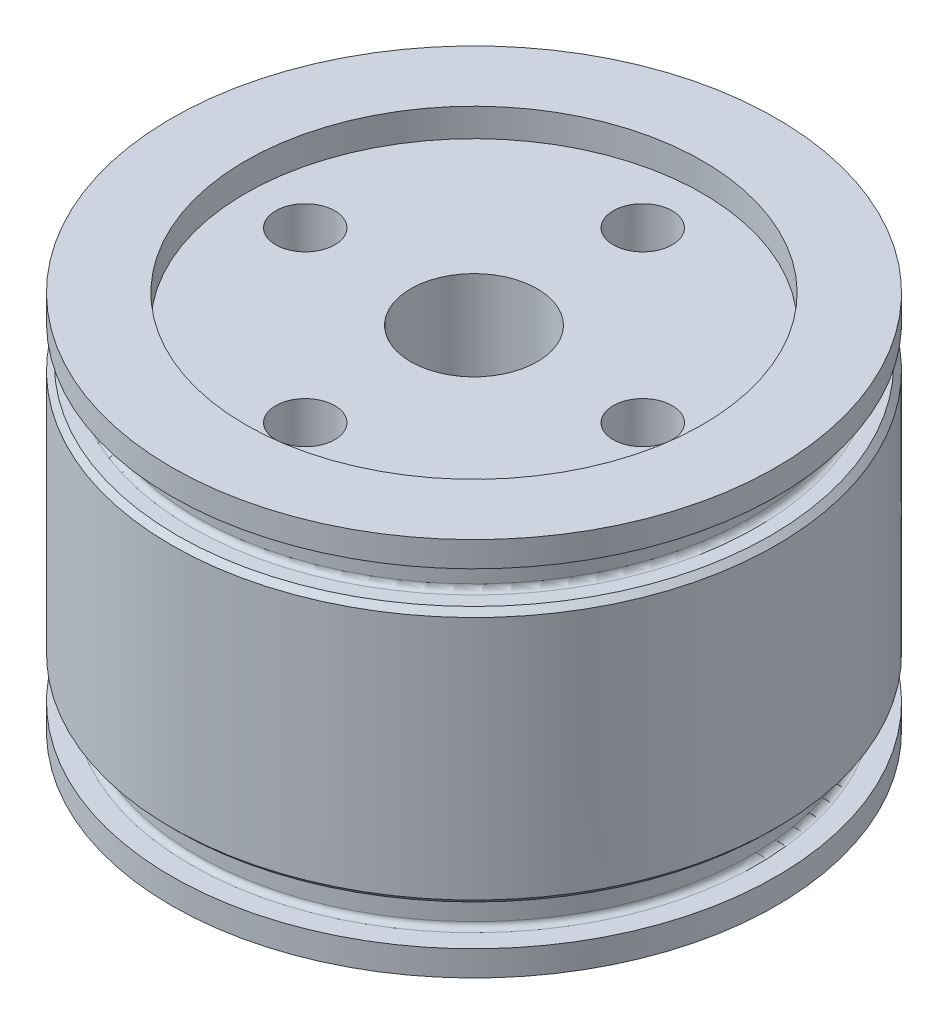
SolidWorks part; units mm, degrees
ref_plane "Front Plane" through (0, 0, 0) normal (0, 0, 1) x (1, 0, 0)
ref_plane "Top Plane" through (0, 0, 0) normal (0, 1, 0) x (1, 0, 0)
ref_plane "Right Plane" through (0, 0, 0) normal (1, 0, 0) x (0, 0, -1)
sketch "Sketch1" plane through (0, 0, 0) normal (0, 1, 0) x (1, 0, 0)
  line L0 (0, 0) -> (0, 12) construction
  circle A0 centre (0, 0) radius 21.5
  circle A1 centre (0, 0) radius 4.5
  circle A2 centre (0, 12) radius 2.1
  circle A3 centre (12, 0) radius 2.1
  circle A4 centre (0, -12) radius 2.1
  circle A5 centre (-12, 0) radius 2.1
  point P15 (0, 0)
  dimension "D1" = 43
  dimension "D2" = 9
  dimension "D5" = 4.2
  dimension "D3" = 12
  dimension "D4" = 12
  dimension "D6" = 4
extrude "Boss-Extrude1" add sketch "Sketch1" along normal blind 27
sketch "Sketch2" plane through (0, 0, 0) normal (0, -1, 0) x (1, 0, 0)
  line L0 (12, -4.1569) -> (15.6, -2.0785)
  line L1 (4.1569, 12) -> (2.0785, 15.6)
  line L2 (2.0785, 15.6) -> (-2.0785, 15.6)
  line L3 (-2.0785, 15.6) -> (-4.1569, 12)
  line L4 (-4.1569, 12) -> (-2.0785, 8.4)
  line L5 (-2.0785, 8.4) -> (2.0785, 8.4)
  line L6 (2.0785, 8.4) -> (4.1569, 12)
  line L7 (15.6, -2.0785) -> (15.6, 2.0785)
  line L8 (15.6, 2.0785) -> (12, 4.1569)
  line L9 (12, 4.1569) -> (8.4, 2.0785)
  line L10 (8.4, 2.0785) -> (8.4, -2.0785)
  line L11 (8.4, -2.0785) -> (12, -4.1569)
  line L12 (-4.1569, -12) -> (-2.0785, -15.6)
  line L13 (-2.0785, -15.6) -> (2.0785, -15.6)
  line L14 (2.0785, -15.6) -> (4.1569, -12)
  line L15 (4.1569, -12) -> (2.0785, -8.4)
  line L16 (2.0785, -8.4) -> (-2.0785, -8.4)
  line L17 (-2.0785, -8.4) -> (-4.1569, -12)
  line L18 (-12, 4.1569) -> (-15.6, 2.0785)
  line L19 (-15.6, 2.0785) -> (-15.6, -2.0785)
  line L20 (-15.6, -2.0785) -> (-12, -4.1569)
  line L21 (-12, -4.1569) -> (-8.4, -2.0785)
  line L22 (-8.4, -2.0785) -> (-8.4, 2.0785)
  line L23 (-8.4, 2.0785) -> (-12, 4.1569)
  circle A0 centre (0, 12) radius 3.6 construction
  point P30 (0, 0)
  dimension "D1" = 7.2
  dimension "D2" = 4
extrude "Cut-Extrude1" cut sketch "Sketch2" against normal blind 22
sketch "Sketch3" plane through (0, 27, 0) normal (0, 1, 0) x (1, 0, 0)
  circle A0 centre (0, 0) radius 16.25
  dimension "D1" = 32.5
extrude "Cut-Extrude2" cut sketch "Sketch3" against normal blind 2
sketch "Sketch5" plane through (0, 0, 0) normal (1, 0, 0) x (0, 0, -1)
  line L0 (0, 0) -> (0, 1.8) construction
  line L2 (0, 27) -> (0, 25.2) construction
  line L3 (16.25, 27) -> (-16.25, 27) construction
  dimension "D1" = 1.8
  dimension "D2" = 1.8
ref_plane "Plane1" through (0, 25.2, 0) normal (0, 1, 0) x (1, 0, 0)
ref_plane "Plane2" through (0, 1.8, 0) normal (0, -1, 0) x (-1, 0, 0)
sketch "Sketch6" plane through (0, 1.8, 0) normal (0, -1, 0) x (-1, 0, 0)
  circle A0 centre (0, 0) radius 21.5
  circle A1 centre (0, 0) radius 19.7
  dimension "D1" = 1.8
extrude "Cut-Extrude3" cut sketch "Sketch6" against normal blind 2.6
sketch "Sketch7" plane through (0, 25.2, 0) normal (0, 1, 0) x (1, 0, 0)
  circle A0 centre (0, 0) radius 21.5
  circle A1 centre (0, 0) radius 19.7
  dimension "D1" = 1.8
extrude "Cut-Extrude4" cut sketch "Sketch7" against normal blind 2.6
fillet "Fillet1" radius 0.4 4 edges at (0, 4.4, -19.7) (0, 1.8, -19.7) (0, 25.2, 19.7) (0, 22.6, 19.7)
chamfer "Chamfer1" distance 0.4 angle 45 2 edges at (0, 4.4, -21.5) (0, 22.6, 21.5)
